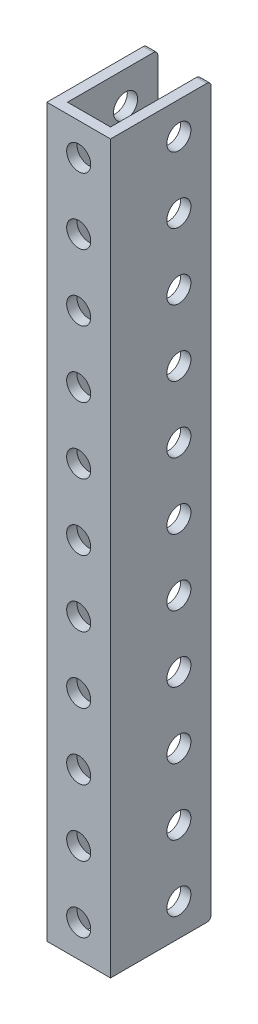
SolidWorks part; units mm, degrees
ref_plane "Front Plane" through (0, 0, 0) normal (0, 0, 1) x (1, 0, 0)
ref_plane "Top Plane" through (0, 0, 0) normal (0, 1, 0) x (1, 0, 0)
ref_plane "Right Plane" through (0, 0, 0) normal (1, 0, 0) x (0, 0, -1)
ref_plane "Plane1" through (4.699, 0, 0) normal (1, 0, 0) x (0, 0, -1)
sketch "Sketch1" plane through (4.699, 0, 0) normal (1, 0, 0) x (0, 0, -1)
  line L0 (-1.524, 0) -> (13.335, 0)
  line L1 (13.335, 0) -> (13.335, 107.315)
  line L2 (13.335, 107.315) -> (-1.524, 107.315)
  line L3 (-1.524, 107.315) -> (-1.524, 0)
extrude "Boss-Extrude1" add sketch "Sketch1" against normal blind 9.398
sketch "Sketch2" plane through (0, 0, 0) normal (0, -1, 0) x (1, 0, 0)
  line L0 (-3.175, -13.335) -> (3.175, -13.335)
  line L1 (3.175, -13.335) -> (3.175, 0)
  line L2 (3.175, 0) -> (-3.175, 0)
  line L3 (-3.175, 0) -> (-3.175, -13.335)
extrude "Cut-Extrude1" cut sketch "Sketch2" against normal through all
hole_wizard "#5 Clearance Hole1" positions "Sketch4" profile "Sketch3" hole size "#5" standard "ANSI Inch"
sketch "Sketch4" plane through (-3.175, 0, 0) normal (1, 0, 0) x (0, 0, -1)
  point P0 (8.5725, 92.7735)
  point P1 (8.5725, 102.5525)
  point P2 (8.5725, 82.9945)
  point P3 (8.5725, 73.2155)
  point P4 (8.5725, 63.4365)
  point P5 (8.5725, 53.6575)
  point P6 (8.5725, 43.8785)
  point P7 (8.5725, 34.0995)
  point P8 (8.5725, 24.3205)
  point P9 (8.5725, 14.5415)
  point P10 (8.5725, 4.7625)
sketch "Sketch3" plane through (-3.175, 92.7735, -8.5725) normal (0, 1, 0) x (0, 0, -1)
  line L0 (0, 0) -> (0, 1.524)
  line L1 (0, 1.524) -> (1.778, 1.524)
  line L2 (1.778, 1.524) -> (1.778, 0)
  line L5 (1.778, 0) -> (0, 0)
  line L11 (0, -6.35) -> (0, 107.95) construction
  dimension "Thru Hole Dia." = 3.556
  dimension "Thru Hole Depth" = 1.524
hole_wizard "#5 Clearance Hole2" positions "Sketch6" profile "Sketch5" hole size "#5" standard "ANSI Inch"
sketch "Sketch6" plane through (0, 0, 1.524) normal (0, 0, 1) x (1, 0, 0)
  point P0 (0, 92.7735)
  point P1 (0, 102.5525)
  point P2 (0, 82.9945)
  point P3 (0, 73.2155)
  point P4 (0, 63.4365)
  point P5 (0, 53.6575)
  point P6 (0, 43.8785)
  point P7 (0, 34.0995)
  point P8 (0, 24.3205)
  point P9 (0, 14.5415)
  point P10 (0, 4.7625)
sketch "Sketch5" plane through (0, 92.7735, 1.524) normal (1, 0, 0) x (0, -1, 0)
  line L0 (0, 0) -> (0, 14.859)
  line L1 (0, 14.859) -> (1.778, 14.859)
  line L2 (1.778, 14.859) -> (1.778, 0)
  line L5 (1.778, 0) -> (0, 0)
  line L11 (0, -6.35) -> (0, 107.95) construction
  dimension "Thru Hole Dia." = 3.556
  dimension "Thru Hole Depth" = 14.859
hole_wizard "#5 Clearance Hole3" positions "Sketch8" profile "Sketch7" hole size "#5" standard "ANSI Inch"
sketch "Sketch8" plane through (4.699, 0, 0) normal (1, 0, 0) x (0, 0, -1)
  point P0 (8.5725, 92.7735)
  point P1 (8.5725, 102.5525)
  point P2 (8.5725, 82.9945)
  point P3 (8.5725, 73.2155)
  point P4 (8.5725, 63.4365)
  point P5 (8.5725, 53.6575)
  point P6 (8.5725, 43.8785)
  point P7 (8.5725, 34.0995)
  point P8 (8.5725, 24.3205)
  point P9 (8.5725, 14.5415)
  point P10 (8.5725, 4.7625)
sketch "Sketch7" plane through (4.699, 92.7735, -8.5725) normal (0, 1, 0) x (0, 0, -1)
  line L0 (0, 0) -> (0, 9.398)
  line L1 (0, 9.398) -> (1.778, 9.398)
  line L2 (1.778, 9.398) -> (1.778, 0)
  line L5 (1.778, 0) -> (0, 0)
  line L11 (0, -6.35) -> (0, 107.95) construction
  dimension "Thru Hole Dia." = 3.556
  dimension "Thru Hole Depth" = 9.398
fillet "Fillet1" radius 0.635 4 edges at (-3.937, 0, -13.335) (-3.937, 107.315, -13.335) (3.937, 107.315, -13.335) (3.937, 0, -13.335)
